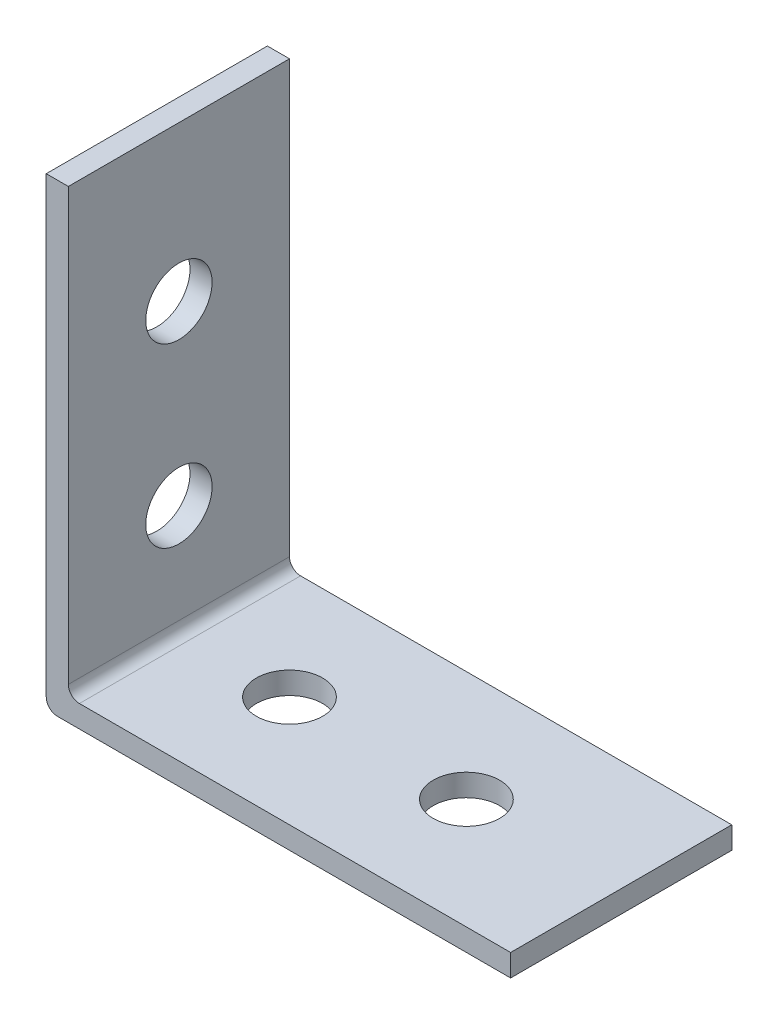
SolidWorks part; units mm, degrees
ref_plane "Ön Düzlem" through (0, 0, 0) normal (0, 0, 1) x (1, 0, 0)
ref_plane "Üst Düzlem" through (0, 0, 0) normal (0, 1, 0) x (1, 0, 0)
ref_plane "Sağ Düzlem" through (0, 0, 0) normal (1, 0, 0) x (0, 0, -1)
sketch "Çizim1" plane through (0, 0, 0) normal (0, 0, 1) x (1, 0, 0)
  line L0 (0, 0) -> (0, 20)
  line L1 (0, 0) -> (20, 0)
  dimension "D1" = 20
  dimension "D2" = 20
extrude "Ekstrüzyon-İnce1" add sketch "Çizim1" along normal mid plane 10 thin thin type one direction wall 1
fillet "Radyus1" radius 0.5 2 edges at (0, 0, 0) (-1, -1, 0)
sketch "Çizim2" plane through (0, 0, 0) normal (1, 0, 0) x (0, 0, -1)
  circle A0 centre (0, 13) radius 1.5
  circle A1 centre (0, 5) radius 1.5
  dimension "D1" = 3
  dimension "D3" = 5
  dimension "D2" = 8
extrude "Kes-Ekstrüzyon1" cut sketch "Çizim2" against normal blind 10
sketch "Çizim4" plane through (0, 0, 0) normal (0, 1, 0) x (1, 0, 0)
  circle A0 centre (5, 0) radius 1.5
  circle A1 centre (13, 0) radius 1.5
  dimension "D1" = 3
  dimension "D3" = 8
  dimension "D2" = 5
extrude "Kes-Ekstrüzyon2" cut sketch "Çizim4" against normal blind 10
scale "Scale3" scale about centroid uniform scaling yes scale factor 0.6
